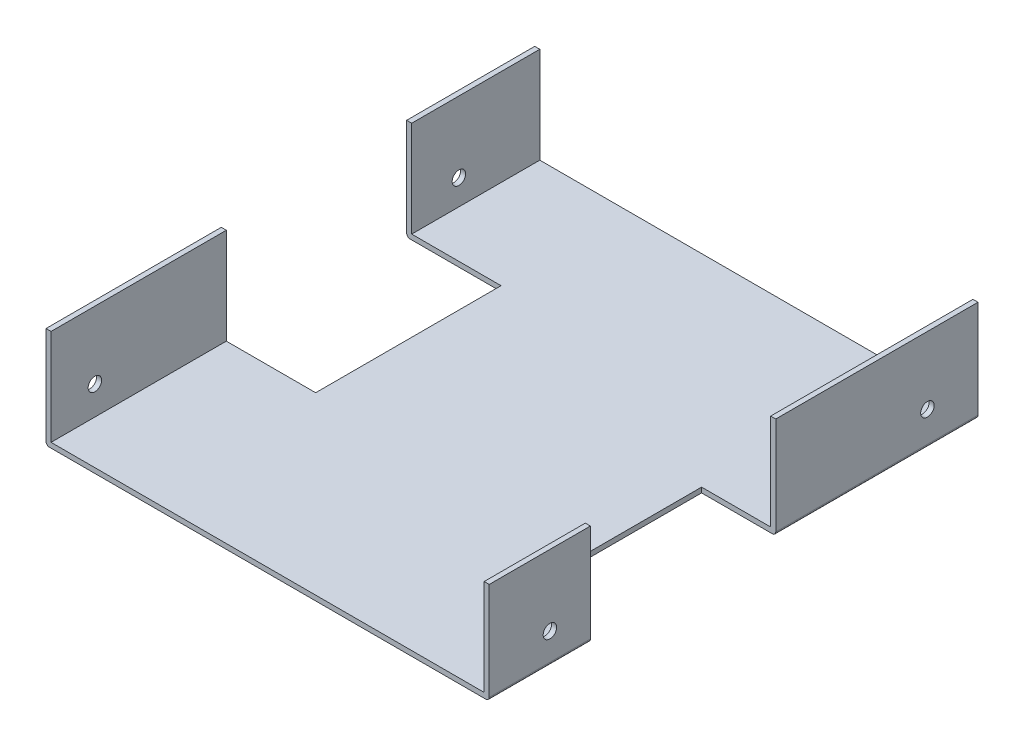
SolidWorks part; units mm, degrees
ref_plane "Alzado" through (0, 0, 0) normal (0, 0, 1) x (1, 0, 0)
ref_plane "Planta" through (0, 0, 0) normal (0, 1, 0) x (1, 0, 0)
ref_plane "Vista lateral" through (0, 0, 0) normal (1, 0, 0) x (0, 0, -1)
sketch "Croquis1" plane through (0, 0, 0) normal (0, 0, 1) x (1, 0, 0)
  line L0 (55, 0) -> (-55, 0) construction
  line L1 (-65.75, 14.5) -> (-64.25, 14.5)
  line L2 (-65.75, 14.5) -> (-65.75, -14.5)
  line L3 (-64.75, -15.5) -> (64.75, -15.5)
  line L4 (65.75, 14.5) -> (65.75, -14.5)
  line L5 (0, -55) -> (0, 55) construction
  line L6 (-64.25, 14.5) -> (-64.25, -14)
  line L7 (-64.25, -14) -> (64.25, -14)
  line L8 (64.25, -14) -> (64.25, 14.5)
  line L9 (64.25, 14.5) -> (65.75, 14.5)
  arc A0 (-65.75, -14.5) -> (-64.75, -15.5) centre (-64.75, -14.5) ccw
  arc A1 (65.75, -14.5) -> (64.75, -15.5) centre (64.75, -14.5) cw
  point P4 (0, -15.5)
  point P5 (-65.75, 0)
  point P16 (-65.75, -15.5)
  point P19 (65.75, -15.5)
  dimension "D6" = 1
  dimension "D7" = 1
  dimension "D1" = 30
  dimension "D2" = 131.5
  dimension "D3" = 1.5
  dimension "D4" = 1.5
  dimension "D5" = 1.5
extrude "Saliente-Extruir1" add sketch "Croquis1" along normal mid plane 145
sketch "Croquis2" plane through (0, -15.5, 0) normal (0, -1, 0) x (1, 0, 0)
  line L0 (-65.75, -34.5) -> (-49.3499, -34.5) construction
  line L1 (-65.75, 72.5) -> (-65.75, -72.5) construction
  line L2 (-64.75, -72.5) -> (64.75, -72.5) construction
  line L3 (-65.75, 20.5) -> (-48.5808, 20.5) construction
  line L4 (-64.75, 72.5) -> (64.75, 72.5) construction
  line L5 (-65.75, 20.5) -> (-37.75, 20.5)
  line L6 (-37.75, 20.5) -> (-37.75, -34.5)
  line L7 (-37.75, -34.5) -> (-65.75, -34.5)
  line L8 (-65.75, -34.5) -> (-65.75, 20.5)
  line L9 (65.75, 42.5) -> (35.9541, 42.5) construction
  line L10 (65.75, 72.5) -> (65.75, -72.5) construction
  line L11 (65.75, -12.5) -> (35.9541, -12.5) construction
  line L12 (65.75, 42.5) -> (43.75, 42.5)
  line L13 (43.75, 42.5) -> (43.75, -12.5)
  line L14 (43.75, -12.5) -> (65.75, -12.5)
  line L15 (65.75, -12.5) -> (65.75, 42.5)
  dimension "D1" = 38
  dimension "D2" = 52
  dimension "D3" = 28
  dimension "D4" = 30
  dimension "D5" = 55
  dimension "D6" = 22
extrude "Cortar-Extruir1" cut sketch "Croquis2" against normal blind 140 and the other way blind 31
sketch "Croquis3" plane through (-65.75, 0, 0) normal (-1, 0, 0) x (0, 0, 1)
  line L0 (72.5, 14.5) -> (72.5, -14.5) construction
  line L1 (72.5, 14.5) -> (20.5, 14.5) construction
  line L2 (-72.5, 14.5) -> (-72.5, -14.5) construction
  line L3 (-34.5, 14.5) -> (-72.5, 14.5) construction
  circle A0 centre (59.5, -5.5) radius 2
  circle A1 centre (-48.5, -6.5) radius 2
  point P0 (59.5, -5.5)
  point P7 (-48.5, -6.5)
  dimension "D3" = 4
  dimension "D6" = 4
  dimension "D1" = 13
  dimension "D2" = 20
  dimension "D4" = 24
  dimension "D5" = 21
extrude "Cortar-Extruir2" cut sketch "Croquis3" against normal blind 81 and the other way blind 53
sketch "Croquis5" plane through (65.75, 0, 0) normal (1, 0, 0) x (0, 0, -1)
  line L0 (-72.5, -14.5) -> (-72.5, 14.5) construction
  line L1 (-72.5, 14.5) -> (-42.5, 14.5) construction
  line L2 (72.5, -14.5) -> (72.5, 14.5) construction
  line L3 (12.5, 14.5) -> (72.5, 14.5) construction
  circle A0 centre (-54.5, -6.5) radius 2
  circle A1 centre (57.5, -5.5) radius 2
  point P0 (-54.5, -6.5)
  point P5 (57.5, -5.5)
  dimension "D3" = 4
  dimension "D6" = 4
  dimension "D1" = 18
  dimension "D2" = 21
  dimension "D4" = 15
  dimension "D5" = 20
extrude "Cortar-Extruir3" cut sketch "Croquis5" against normal blind 81
